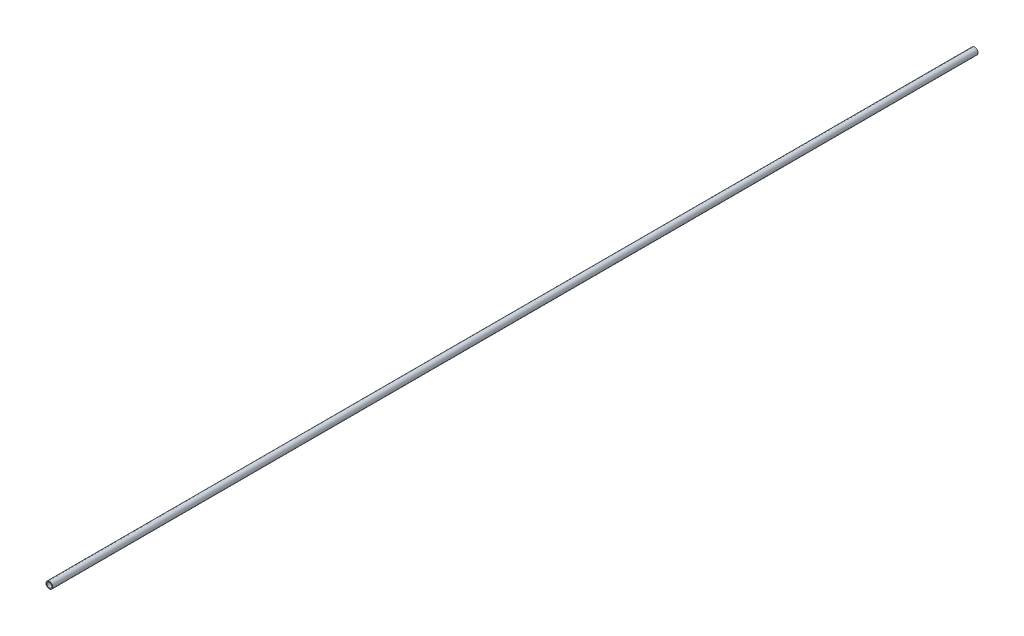
SolidWorks part; units mm, degrees
ref_plane "Front Plane" through (0, 0, 0) normal (0, 0, 1) x (1, 0, 0)
ref_plane "Top Plane" through (0, 0, 0) normal (0, 1, 0) x (1, 0, 0)
ref_plane "Right Plane" through (0, 0, 0) normal (1, 0, 0) x (0, 0, -1)
sketch "Sketch1" plane through (0, 0, 0) normal (0, 0, 1) x (1, 0, 0)
  circle A0 centre (0, 0) radius 4.7625
  circle A1 centre (0, 0) radius 3.5179
  dimension "D1" = 9.525
  dimension "D2" = 1.2446
extrude "Boss-Extrude1" add sketch "Sketch1" along normal blind 1326.3732
